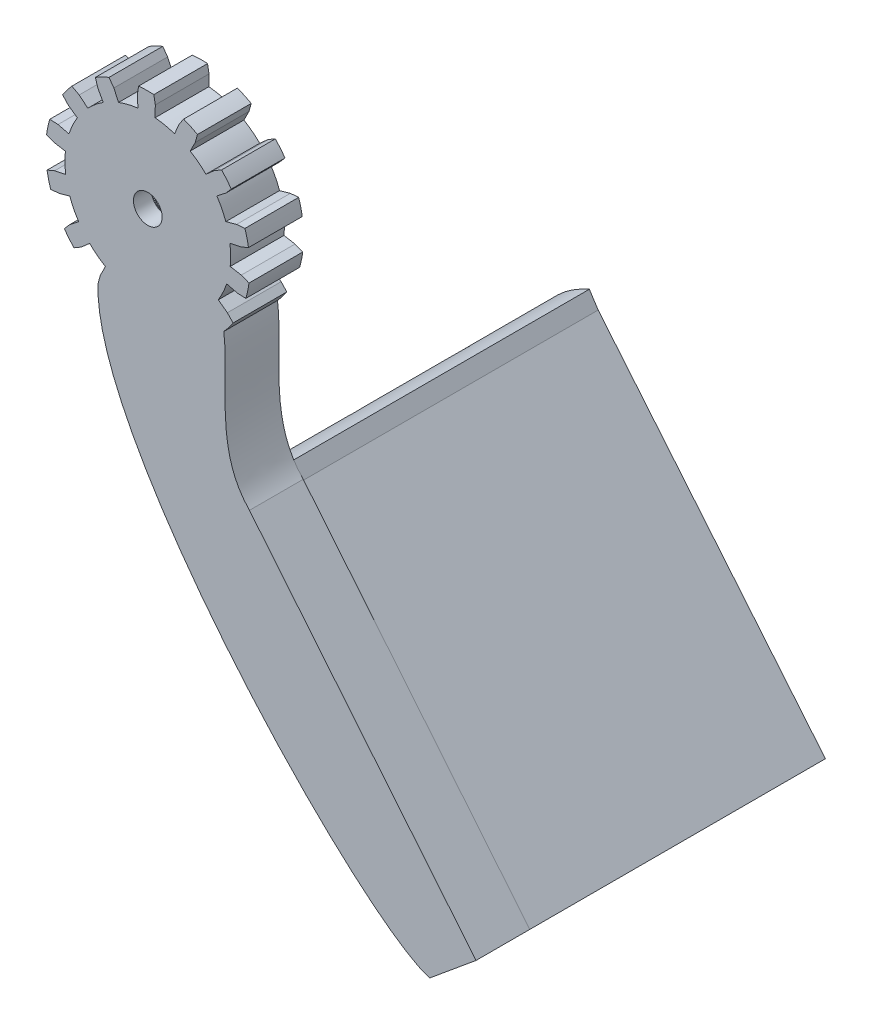
SolidWorks part; units mm, degrees
ref_plane "Front Plane" through (0, 0, 0) normal (0, 0, 1) x (1, 0, 0)
ref_plane "Top Plane" through (0, 0, 0) normal (0, 1, 0) x (1, 0, 0)
ref_plane "Right Plane" through (0, 0, 0) normal (1, 0, 0) x (0, 0, -1)
sketch "Sketch2" plane through (0, 0, 0) normal (0, 0, 1) x (1, 0, 0)
  line L0 (11.1946, 10) -> (11.1946, 10.6054) construction
  line L669 (17.6878, 7.31) -> (18.6279, 8.138)
  line L670 (18.6279, 8.138) -> (19.4304, 8.6044)
  line L671 (21.6272, -0.4657) -> (22.4922, -0.8024)
  line L672 (20.3937, -0.247) -> (21.6272, -0.4657)
  line L673 (20.3589, 1.9784) -> (21.5849, 2.2356)
  line L674 (21.5849, 2.2356) -> (22.439, 2.5991)
  line L675 (21.1094, 4.1784) -> (22.0348, 4.2505)
  line L676 (19.9032, 3.8403) -> (21.1094, 4.1784)
  line L677 (18.9062, 5.8303) -> (19.8993, 6.5939)
  line L678 (19.8993, 6.5939) -> (20.511, 7.292)
  line L679 (14.4587, -7.9329) -> (14.9822, -9.071)
  line L680 (14.9822, -9.071) -> (15.5266, -9.8227)
  line L681 (16.7705, -8.175) -> (17.0467, -9.0612)
  line L682 (16.1724, -7.0743) -> (16.7705, -8.175)
  line L683 (17.8907, -5.6595) -> (18.8561, -6.4578)
  line L684 (18.8561, -6.4578) -> (19.6729, -6.8988)
  line L685 (20.0786, -4.8746) -> (20.7119, -5.5532)
  line L686 (19.0622, -4.1424) -> (20.0786, -4.8746)
  line L687 (19.9964, -2.1222) -> (21.2126, -2.4225)
  line L688 (21.2126, -2.4225) -> (22.1398, -2.4655)
  line L689 (3.4829, -4.3861) -> (2.4899, -5.1497)
  line L690 (2.4899, -5.1497) -> (1.8781, -5.8478)
  line L691 (3.7613, -6.6939) -> (2.9588, -7.1603)
  line L692 (4.7013, -5.8658) -> (3.7613, -6.6939)
  line L693 (6.463, -7.2262) -> (5.8996, -8.3451)
  line L694 (5.8996, -8.3451) -> (5.6513, -9.2394)
  line L695 (7.7151, -9.1846) -> (7.1944, -9.953)
  line L696 (8.2027, -8.0307) -> (7.7151, -9.1846)
  line L697 (10.3802, -8.492) -> (10.3581, -9.7445)
  line L698 (10.3581, -9.7445) -> (10.5224, -10.6581)
  line L699 (12.358, -9.7133) -> (12.2223, -10.6315)
  line L700 (12.2967, -8.462) -> (12.358, -9.7133)
  line L701 (2.3105, 6.3188) -> (1.6772, 6.9974)
  line L702 (3.327, 5.5866) -> (2.3105, 6.3188)
  line L703 (2.3927, 3.5664) -> (1.1765, 3.8667)
  line L704 (1.1765, 3.8667) -> (0.2493, 3.9097)
  line L705 (0.762, 1.9099) -> (-0.103, 2.2465)
  line L706 (1.9955, 1.6912) -> (0.762, 1.9099)
  line L707 (2.0303, -0.5343) -> (0.8042, -0.7914)
  line L708 (0.8042, -0.7914) -> (-0.0498, -1.1549)
  line L709 (1.2798, -2.7343) -> (0.3543, -2.8063)
  line L710 (2.486, -2.3961) -> (1.2798, -2.7343)
  line L711 (12.009, 9.9362) -> (12.0311, 11.1887)
  line L712 (12.0311, 11.1887) -> (11.8667, 12.1023)
  line L713 (10.0311, 11.1574) -> (10.1668, 12.0757)
  line L714 (10.0924, 9.9062) -> (10.0311, 11.1574)
  line L715 (7.9305, 9.377) -> (7.4069, 10.5151)
  line L716 (7.4069, 10.5151) -> (6.8625, 11.2669)
  line L717 (5.6186, 9.6192) -> (5.3425, 10.5054)
  line L718 (6.2167, 8.5185) -> (5.6186, 9.6192)
  line L719 (4.4985, 7.1037) -> (3.533, 7.9019)
  line L720 (3.533, 7.9019) -> (2.7163, 8.343)
  line L721 (15.9262, 8.6703) -> (16.4895, 9.7892)
  line L722 (16.4895, 9.7892) -> (16.7378, 10.6836)
  line L723 (14.6741, 10.6288) -> (15.1948, 11.3972)
  line L724 (14.1864, 9.4749) -> (14.6741, 10.6288)
  arc A141 (20.511, 7.292) -> (19.4304, 8.6044) centre (11.1946, 0.7221) ccw
  arc A145 (17.6878, 7.31) -> (15.9262, 8.6703) centre (11.1946, 0.7221) ccw
  arc A149 (22.439, 2.5991) -> (22.0348, 4.2505) centre (11.1946, 0.7221) ccw
  arc A151 (22.1398, -2.4655) -> (22.4922, -0.8024) centre (11.1946, 0.7221) ccw
  arc A152 (19.6729, -6.8988) -> (20.7119, -5.5532) centre (11.1946, 0.7221) ccw
  arc A153 (15.5266, -9.8227) -> (17.0467, -9.0612) centre (11.1946, 0.7221) ccw
  arc A154 (10.5224, -10.6581) -> (12.2223, -10.6315) centre (11.1946, 0.7221) ccw
  arc A155 (5.6513, -9.2394) -> (7.1944, -9.953) centre (11.1946, 0.7221) ccw
  arc A156 (1.8781, -5.8478) -> (2.9588, -7.1603) centre (11.1946, 0.7221) ccw
  arc A157 (-0.0498, -1.1549) -> (0.3543, -2.8063) centre (11.1946, 0.7221) ccw
  arc A158 (0.2493, 3.9097) -> (-0.103, 2.2465) centre (11.1946, 0.7221) ccw
  arc A159 (2.7163, 8.343) -> (1.6772, 6.9974) centre (11.1946, 0.7221) ccw
  arc A160 (6.8625, 11.2669) -> (5.3425, 10.5054) centre (11.1946, 0.7221) ccw
  arc A161 (11.8667, 12.1023) -> (10.1668, 12.0757) centre (11.1946, 0.7221) ccw
  arc A162 (16.7378, 10.6836) -> (15.1948, 11.3972) centre (11.1946, 0.7221) ccw
  arc A163 (19.9032, 3.8403) -> (18.9062, 5.8303) centre (11.1946, 0.7221) ccw
  arc A164 (20.3937, -0.247) -> (20.3589, 1.9784) centre (11.1946, 0.7221) ccw
  arc A165 (19.0622, -4.1424) -> (19.9964, -2.1222) centre (11.1946, 0.7221) ccw
  arc A166 (16.1724, -7.0743) -> (17.8907, -5.6595) centre (11.1946, 0.7221) ccw
  arc A167 (12.2967, -8.462) -> (14.4587, -7.9329) centre (11.1946, 0.7221) ccw
  arc A168 (8.2027, -8.0307) -> (10.3802, -8.492) centre (11.1946, 0.7221) ccw
  arc A169 (4.7013, -5.8658) -> (6.463, -7.2262) centre (11.1946, 0.7221) ccw
  arc A170 (2.486, -2.3961) -> (3.4829, -4.3861) centre (11.1946, 0.7221) ccw
  arc A171 (1.9955, 1.6912) -> (2.0303, -0.5343) centre (11.1946, 0.7221) ccw
  arc A172 (3.327, 5.5866) -> (2.3927, 3.5664) centre (11.1946, 0.7221) ccw
  arc A173 (6.2167, 8.5185) -> (4.4985, 7.1037) centre (11.1946, 0.7221) ccw
  arc A174 (10.0924, 9.9062) -> (7.9305, 9.377) centre (11.1946, 0.7221) ccw
  arc A175 (14.1864, 9.4749) -> (12.009, 9.9362) centre (11.1946, 0.7221) ccw
extrude "Boss-Extrude1" add sketch "Sketch2" against normal blind 4 and the other way blind 2
sketch "Sketch3" plane through (0, 0, 2) normal (0, 0, 1) x (1, 0, 0)
  circle A0 centre (11.1946, 0) radius 3.5
  dimension "D1" = 7
extrude "Boss-Extrude2" add sketch "Sketch3" against normal blind 2
sketch "Sketch4" plane through (0, 0, 2) normal (0, 0, 1) x (1, 0, 0)
  circle A0 centre (11.1946, 0.7221) radius 4.295 construction
sketch "Sketch5" plane through (0, 0, 2) normal (0, 0, 1) x (1, 0, 0)
  line L0 (10.0276, -11.444) -> (15.4878, -11.444) construction
  line L1 (4.4176, 11.5) -> (18.1778, 11.5) construction
  line L5 (22.5424, -22.747) -> (47.8352, -53.6184)
  line L7 (42.6592, -57.9021) -> (47.8352, -53.6184)
  line L25 (15.9262, 8.6703) -> (16.4895, 9.7892)
  line L35 (3.4829, -4.3861) -> (2.4899, -5.1497)
  line L45 (15.1948, 11.3972) -> (14.6741, 10.6288)
  line L55 (14.6741, 10.6288) -> (14.1864, 9.4749)
  line L98 (22.0348, 4.2505) -> (21.1094, 4.1784)
  line L102 (12.009, 9.9362) -> (12.0311, 11.1887)
  line L104 (14.9822, -9.071) -> (15.5266, -9.8227)
  line L105 (14.9822, -9.071) -> (15.5266, -9.8227)
  line L110 (2.4899, -5.1497) -> (1.8781, -5.8478)
  line L114 (5.8996, -8.3451) -> (5.6513, -9.2394)
  line L124 (2.3927, 3.5664) -> (1.1765, 3.8667)
  line L126 (1.1765, 3.8667) -> (0.2493, 3.9097)
  line L130 (0.8042, -0.7914) -> (-0.0498, -1.1549)
  line L140 (5.3425, 10.5054) -> (5.6186, 9.6192)
  line L146 (16.4895, 9.7892) -> (16.7378, 10.6836)
  line L153 (12.0311, 11.1887) -> (11.8667, 12.1023)
  line L157 (10.1668, 12.0757) -> (10.0311, 11.1574)
  line L161 (10.0311, 11.1574) -> (10.0924, 9.9062)
  line L196 (7.9305, 9.377) -> (7.4069, 10.5151)
  line L198 (7.4069, 10.5151) -> (6.8625, 11.2669)
  line L200 (5.6186, 9.6192) -> (6.2167, 8.5185)
  line L202 (4.4985, 7.1037) -> (3.533, 7.9019)
  line L204 (3.533, 7.9019) -> (2.7163, 8.343)
  line L206 (1.6772, 6.9974) -> (2.3105, 6.3188)
  line L208 (2.3105, 6.3188) -> (3.327, 5.5866)
  line L210 (-0.103, 2.2465) -> (0.762, 1.9099)
  line L212 (0.762, 1.9099) -> (1.9955, 1.6912)
  line L214 (2.0303, -0.5343) -> (0.8042, -0.7914)
  line L216 (0.3543, -2.8063) -> (1.2798, -2.7343)
  line L218 (1.2798, -2.7343) -> (2.486, -2.3961)
  line L220 (2.9588, -7.1603) -> (3.7613, -6.6939)
  line L222 (3.7613, -6.6939) -> (4.7013, -5.8658)
  line L224 (6.463, -7.2262) -> (5.8996, -8.3451)
  line L226 (7.1944, -9.953) -> (7.7151, -9.1846)
  line L227 (7.1944, -9.953) -> (7.7151, -9.1846)
  line L228 (7.7151, -9.1846) -> (8.2027, -8.0307)
  line L229 (7.7151, -9.1846) -> (8.2027, -8.0307)
  line L230 (10.3802, -8.492) -> (10.3581, -9.7445)
  line L231 (10.3802, -8.492) -> (10.3581, -9.7445)
  line L232 (10.3581, -9.7445) -> (10.5224, -10.6581)
  line L233 (10.3581, -9.7445) -> (10.5224, -10.6581)
  line L234 (12.2223, -10.6315) -> (12.358, -9.7133)
  line L235 (12.2223, -10.6315) -> (12.358, -9.7133)
  line L236 (12.358, -9.7133) -> (12.2967, -8.462)
  line L237 (12.358, -9.7133) -> (12.2967, -8.462)
  line L238 (14.4587, -7.9329) -> (14.9822, -9.071)
  line L239 (14.4587, -7.9329) -> (14.9822, -9.071)
  line L240 (17.0467, -9.0612) -> (16.7705, -8.175)
  line L241 (17.0467, -9.0612) -> (16.7705, -8.175)
  line L242 (16.7705, -8.175) -> (16.1724, -7.0743)
  line L243 (16.7705, -8.175) -> (16.1724, -7.0743)
  line L244 (17.8907, -5.6595) -> (18.8561, -6.4578)
  line L245 (17.8907, -5.6595) -> (18.8561, -6.4578)
  line L246 (18.8561, -6.4578) -> (19.6729, -6.8988)
  line L247 (18.8561, -6.4578) -> (19.6729, -6.8988)
  line L248 (20.7119, -5.5532) -> (20.0786, -4.8746)
  line L250 (20.0786, -4.8746) -> (19.0622, -4.1424)
  line L252 (19.9964, -2.1222) -> (21.2126, -2.4225)
  line L254 (21.2126, -2.4225) -> (22.1398, -2.4655)
  line L256 (22.4922, -0.8024) -> (21.6272, -0.4657)
  line L258 (21.6272, -0.4657) -> (20.3937, -0.247)
  line L260 (20.3589, 1.9784) -> (21.5849, 2.2356)
  line L262 (21.5849, 2.2356) -> (22.439, 2.5991)
  line L264 (21.1094, 4.1784) -> (19.9032, 3.8403)
  line L266 (18.9062, 5.8303) -> (19.8993, 6.5939)
  line L268 (19.8993, 6.5939) -> (20.511, 7.292)
  line L270 (19.4304, 8.6044) -> (18.6279, 8.138)
  line L272 (18.6279, 8.138) -> (17.6878, 7.31)
  arc A14 (17.6878, 7.31) -> (15.9262, 8.6703) centre (11.1946, 0.7221) ccw
  arc A36 (16.7378, 10.6836) -> (15.1948, 11.3972) centre (11.1946, 0.7221) ccw
  arc A44 (14.1864, 9.4749) -> (12.009, 9.9362) centre (11.1946, 0.7221) ccw
  arc A52 (11.8667, 12.1023) -> (10.1668, 12.0757) centre (11.1946, 0.7221) ccw
  arc A98 (10.0924, 9.9062) -> (7.9305, 9.377) centre (11.1946, 0.7221) ccw
  arc A100 (6.8625, 11.2669) -> (5.3425, 10.5054) centre (11.1946, 0.7221) ccw
  arc A102 (6.2167, 8.5185) -> (4.4985, 7.1037) centre (11.1946, 0.7221) ccw
  arc A104 (2.7163, 8.343) -> (1.6772, 6.9974) centre (11.1946, 0.7221) ccw
  arc A106 (3.327, 5.5866) -> (2.3927, 3.5664) centre (11.1946, 0.7221) ccw
  arc A108 (0.2493, 3.9097) -> (-0.103, 2.2465) centre (11.1946, 0.7221) ccw
  arc A110 (1.9955, 1.6912) -> (2.0303, -0.5343) centre (11.1946, 0.7221) ccw
  arc A112 (-0.0498, -1.1549) -> (0.3543, -2.8063) centre (11.1946, 0.7221) ccw
  arc A114 (2.486, -2.3961) -> (3.4829, -4.3861) centre (11.1946, 0.7221) ccw
  arc A116 (1.8781, -5.8478) -> (2.9588, -7.1603) centre (11.1946, 0.7221) ccw
  arc A118 (4.7013, -5.8658) -> (6.463, -7.2262) centre (11.1946, 0.7221) ccw
  arc A120 (5.6513, -9.2394) -> (7.1944, -9.953) centre (11.1946, 0.7221) ccw
  arc A121 (5.6513, -9.2394) -> (7.1944, -9.953) centre (11.1946, 0.7221) ccw
  arc A122 (8.2027, -8.0307) -> (10.3802, -8.492) centre (11.1946, 0.7221) ccw
  arc A123 (8.2027, -8.0307) -> (10.3802, -8.492) centre (11.1946, 0.7221) ccw
  arc A124 (10.5224, -10.6581) -> (12.2223, -10.6315) centre (11.1946, 0.7221) ccw
  arc A125 (10.5224, -10.6581) -> (12.2223, -10.6315) centre (11.1946, 0.7221) ccw
  arc A126 (12.2967, -8.462) -> (14.4587, -7.9329) centre (11.1946, 0.7221) ccw
  arc A127 (12.2967, -8.462) -> (14.4587, -7.9329) centre (11.1946, 0.7221) ccw
  arc A128 (15.5266, -9.8227) -> (17.0467, -9.0612) centre (11.1946, 0.7221) ccw
  arc A129 (15.5266, -9.8227) -> (17.0467, -9.0612) centre (11.1946, 0.7221) ccw
  arc A130 (16.1724, -7.0743) -> (17.8907, -5.6595) centre (11.1946, 0.7221) ccw
  arc A131 (16.1724, -7.0743) -> (17.8907, -5.6595) centre (11.1946, 0.7221) ccw
  arc A132 (19.6729, -6.8988) -> (20.7119, -5.5532) centre (11.1946, 0.7221) ccw
  arc A134 (19.0622, -4.1424) -> (19.9964, -2.1222) centre (11.1946, 0.7221) ccw
  arc A136 (22.1398, -2.4655) -> (22.4922, -0.8024) centre (11.1946, 0.7221) ccw
  arc A138 (20.3937, -0.247) -> (20.3589, 1.9784) centre (11.1946, 0.7221) ccw
  arc A140 (22.439, 2.5991) -> (22.0348, 4.2505) centre (11.1946, 0.7221) ccw
  arc A142 (19.9032, 3.8403) -> (18.9062, 5.8303) centre (11.1946, 0.7221) ccw
  arc A144 (20.511, 7.292) -> (19.4304, 8.6044) centre (11.1946, 0.7221) ccw
  spline S0 degree 3 poles (19.6729, -6.8988) (20.3229, -11.6834) (18.5625, -18.6883) (22.5424, -22.747) knots 0 0 0 0 1 1 1 1
  spline S1 degree 3 poles (42.6592, -57.9021) (34.7948, -55.7125) (4.8913, -24.2389) (5.6513, -9.2394) knots 0.222416 0.222416 0.222416 0.222416 1 1 1 1
  dimension "D1" = 0
extrude "Boss-Extrude3" add sketch "Sketch5" against normal up to surface (6 mm away) up to face at (11.1946, 0.7221, -4)
sketch "Sketch6" plane through (0, 0, -4) normal (0, 0, -1) x (-1, 0, 0)
  line L0 (-47.8352, -53.6184) -> (-22.4699, -22.9253)
  line L24 (-2.4899, -5.1497) -> (-3.4829, -4.3861)
  line L32 (-22.5424, -22.747) -> (-47.8352, -53.6184)
  line L86 (-47.8352, -53.6184) -> (-42.6592, -57.9021)
  line L88 (-47.8352, -53.6184) -> (-42.6592, -57.9021)
  line L141 (-16.7378, 10.6836) -> (-16.4895, 9.7892)
  line L147 (-5.6186, 9.6192) -> (-5.3425, 10.5054)
  line L157 (0.0498, -1.1549) -> (-0.8042, -0.7914)
  line L161 (-0.2493, 3.9097) -> (-1.1765, 3.8667)
  line L163 (-1.1765, 3.8667) -> (-2.3927, 3.5664)
  line L173 (-5.6513, -9.2394) -> (-5.8996, -8.3451)
  line L177 (-1.8781, -5.8478) -> (-2.4899, -5.1497)
  line L206 (-21.1094, 4.1784) -> (-22.0348, 4.2505)
  line L208 (-17.6878, 7.31) -> (-18.6279, 8.138)
  line L210 (-18.6279, 8.138) -> (-19.4304, 8.6044)
  line L212 (-20.511, 7.292) -> (-19.8993, 6.5939)
  line L214 (-19.8993, 6.5939) -> (-18.9062, 5.8303)
  line L216 (-19.9032, 3.8403) -> (-21.1094, 4.1784)
  line L218 (-22.439, 2.5991) -> (-21.5849, 2.2356)
  line L220 (-21.5849, 2.2356) -> (-20.3589, 1.9784)
  line L222 (-20.3937, -0.247) -> (-21.6272, -0.4657)
  line L224 (-21.6272, -0.4657) -> (-22.4922, -0.8024)
  line L226 (-22.1398, -2.4655) -> (-21.2126, -2.4225)
  line L228 (-21.2126, -2.4225) -> (-19.9964, -2.1222)
  line L230 (-19.0622, -4.1424) -> (-20.0786, -4.8746)
  line L232 (-20.0786, -4.8746) -> (-20.7119, -5.5532)
  line L256 (-5.8996, -8.3451) -> (-6.463, -7.2262)
  line L258 (-4.7013, -5.8658) -> (-3.7613, -6.6939)
  line L260 (-3.7613, -6.6939) -> (-2.9588, -7.1603)
  line L262 (-2.486, -2.3961) -> (-1.2798, -2.7343)
  line L264 (-1.2798, -2.7343) -> (-0.3543, -2.8063)
  line L266 (-0.8042, -0.7914) -> (-2.0303, -0.5343)
  line L268 (-1.9955, 1.6912) -> (-0.762, 1.9099)
  line L270 (-0.762, 1.9099) -> (0.103, 2.2465)
  line L272 (-3.327, 5.5866) -> (-2.3105, 6.3188)
  line L274 (-2.3105, 6.3188) -> (-1.6772, 6.9974)
  line L276 (-2.7163, 8.343) -> (-3.533, 7.9019)
  line L278 (-3.533, 7.9019) -> (-4.4985, 7.1037)
  line L280 (-6.2167, 8.5185) -> (-5.6186, 9.6192)
  line L282 (-6.8625, 11.2669) -> (-7.4069, 10.5151)
  line L284 (-7.4069, 10.5151) -> (-7.9305, 9.377)
  line L286 (-10.0924, 9.9062) -> (-10.0311, 11.1574)
  line L288 (-10.0311, 11.1574) -> (-10.1668, 12.0757)
  line L290 (-11.8667, 12.1023) -> (-12.0311, 11.1887)
  line L292 (-12.0311, 11.1887) -> (-12.009, 9.9362)
  line L294 (-14.1864, 9.4749) -> (-14.6741, 10.6288)
  line L296 (-14.6741, 10.6288) -> (-15.1948, 11.3972)
  line L298 (-16.4895, 9.7892) -> (-15.9262, 8.6703)
  arc A44 (-15.9262, 8.6703) -> (-17.6878, 7.31) centre (-11.1946, 0.7221) ccw
  arc A85 (-19.4304, 8.6044) -> (-20.511, 7.292) centre (-11.1946, 0.7221) ccw
  arc A87 (-18.9062, 5.8303) -> (-19.9032, 3.8403) centre (-11.1946, 0.7221) ccw
  arc A89 (-22.0348, 4.2505) -> (-22.439, 2.5991) centre (-11.1946, 0.7221) ccw
  arc A91 (-20.3589, 1.9784) -> (-20.3937, -0.247) centre (-11.1946, 0.7221) ccw
  arc A93 (-22.4922, -0.8024) -> (-22.1398, -2.4655) centre (-11.1946, 0.7221) ccw
  arc A95 (-19.9964, -2.1222) -> (-19.0622, -4.1424) centre (-11.1946, 0.7221) ccw
  arc A97 (-20.7119, -5.5532) -> (-19.6729, -6.8988) centre (-11.1946, 0.7221) ccw
  arc A111 (-6.463, -7.2262) -> (-4.7013, -5.8658) centre (-11.1946, 0.7221) ccw
  arc A113 (-2.9588, -7.1603) -> (-1.8781, -5.8478) centre (-11.1946, 0.7221) ccw
  arc A115 (-3.4829, -4.3861) -> (-2.486, -2.3961) centre (-11.1946, 0.7221) ccw
  arc A117 (-0.3543, -2.8063) -> (0.0498, -1.1549) centre (-11.1946, 0.7221) ccw
  arc A119 (-2.0303, -0.5343) -> (-1.9955, 1.6912) centre (-11.1946, 0.7221) ccw
  arc A121 (0.103, 2.2465) -> (-0.2493, 3.9097) centre (-11.1946, 0.7221) ccw
  arc A123 (-2.3927, 3.5664) -> (-3.327, 5.5866) centre (-11.1946, 0.7221) ccw
  arc A125 (-1.6772, 6.9974) -> (-2.7163, 8.343) centre (-11.1946, 0.7221) ccw
  arc A127 (-4.4985, 7.1037) -> (-6.2167, 8.5185) centre (-11.1946, 0.7221) ccw
  arc A129 (-5.3425, 10.5054) -> (-6.8625, 11.2669) centre (-11.1946, 0.7221) ccw
  arc A131 (-7.9305, 9.377) -> (-10.0924, 9.9062) centre (-11.1946, 0.7221) ccw
  arc A133 (-10.1668, 12.0757) -> (-11.8667, 12.1023) centre (-11.1946, 0.7221) ccw
  arc A135 (-12.009, 9.9362) -> (-14.1864, 9.4749) centre (-11.1946, 0.7221) ccw
  arc A137 (-15.1948, 11.3972) -> (-16.7378, 10.6836) centre (-11.1946, 0.7221) ccw
  spline S0 degree 2 poles (-21.4843, -21.4053) (-15.4608, -24.0435) (-14.9342, -30.624) knots 0 0 0 1 1 1
  spline S1 degree 1 poles (-21.4843, -21.4053) (-22.4699, -22.9253) knots 0 0 1 1
  spline S2 degree 3 poles (2049.8624, 2090.3676) (-2456.4303, -2304.2529) (2542.9708, 2077.6557) (-2472.1397, -1711.8889) knots -2.171759 -2.171759 -2.171759 -2.171759 3.412488 3.412488 3.412488 3.412488 only from (-42.6592, -57.9021) to (-5.6513, -9.2394) construction
  spline S4 degree 3 poles (-42.6592, -57.9021) (-37.7406, -56.5327) (-24.2012, -43.7085) (-14.9342, -30.624) knots 0.222416 0.222416 0.222416 0.222416 0.708738 0.708738 0.708738 0.708738
  spline S6 degree 3 poles (837.4917, -521.9394) (-890.8689, 582.5241) (863.9486, -583.6115) (-915.3049, 427.7689) knots -4.426358 -4.426358 -4.426358 -4.426358 5.086809 5.086809 5.086809 5.086809 only from (-19.6729, -6.8988) to (-22.5424, -22.747)
  spline S7 degree 3 poles (630.5716, 681.5226) (-904.3184, -885.7477) (926.9509, 733.4176) (-861.5437, -526.3532) knots -1.362805 -1.362805 -1.362805 -1.362805 2.601902 2.601902 2.601902 2.601902 only from (-42.6592, -57.9021) to (-5.6513, -9.2394)
  dimension "D1" = 0
extrude "Boss-Extrude4" add sketch "Sketch6" along normal blind 33
sketch "Sketch7" plane through (0, 0, -4) normal (0, 0, -1) x (-1, 0, 0)
  line L200 (-13.2071, 2.8678) -> (-13.1729, 2.7035)
  line L201 (-13.0453, 2.8231) -> (-13.2071, 2.8678)
  line L202 (-13.0691, 2.9892) -> (-13.0453, 2.8231)
  line L203 (-12.9105, 2.9344) -> (-13.0691, 2.9892)
  line L204 (-12.9238, 3.1017) -> (-12.9105, 2.9344)
  line L205 (-12.769, 3.0371) -> (-12.9238, 3.1017)
  line L206 (-12.7717, 3.2048) -> (-12.769, 3.0371)
  line L207 (-12.6213, 3.1306) -> (-12.7717, 3.2048)
  line L208 (-12.6135, 3.2982) -> (-12.6213, 3.1306)
  line L209 (-12.468, 3.2147) -> (-12.6135, 3.2982)
  line L210 (-12.4497, 3.3814) -> (-12.468, 3.2147)
  line L211 (-12.3097, 3.289) -> (-12.4497, 3.3814)
  line L212 (-12.281, 3.4543) -> (-12.3097, 3.289)
  line L213 (-12.1471, 3.3532) -> (-12.281, 3.4543)
  line L214 (-12.108, 3.5163) -> (-12.1471, 3.3532)
  line L215 (-11.9807, 3.407) -> (-12.108, 3.5163)
  line L216 (-11.9315, 3.5674) -> (-11.9807, 3.407)
  line L217 (-11.8113, 3.4504) -> (-11.9315, 3.5674)
  line L218 (-11.7521, 3.6073) -> (-11.8113, 3.4504)
  line L219 (-11.6396, 3.4829) -> (-11.7521, 3.6073)
  line L220 (-11.5706, 3.6359) -> (-11.6396, 3.4829)
  line L221 (-11.4661, 3.5047) -> (-11.5706, 3.6359)
  line L222 (-11.3877, 3.653) -> (-11.4661, 3.5047)
  line L223 (-11.2916, 3.5155) -> (-11.3877, 3.653)
  line L224 (-11.204, 3.6586) -> (-11.2916, 3.5155)
  line L225 (-11.1167, 3.5153) -> (-11.204, 3.6586)
  line L226 (-11.0204, 3.6527) -> (-11.1167, 3.5153)
  line L227 (-10.9422, 3.5042) -> (-11.0204, 3.6527)
  line L228 (-10.8374, 3.6352) -> (-10.9422, 3.5042)
  line L229 (-10.7688, 3.4821) -> (-10.8374, 3.6352)
  line L230 (-10.656, 3.6063) -> (-10.7688, 3.4821)
  line L231 (-10.5971, 3.4492) -> (-10.656, 3.6063)
  line L232 (-10.4767, 3.566) -> (-10.5971, 3.4492)
  line L233 (-10.4278, 3.4055) -> (-10.4767, 3.566)
  line L234 (-10.3003, 3.5146) -> (-10.4278, 3.4055)
  line L235 (-10.2616, 3.3513) -> (-10.3003, 3.5146)
  line L236 (-10.1275, 3.4522) -> (-10.2616, 3.3513)
  line L237 (-10.0991, 3.2868) -> (-10.1275, 3.4522)
  line L238 (-9.9589, 3.379) -> (-10.0991, 3.2868)
  line L239 (-9.9409, 3.2122) -> (-9.9589, 3.379)
  line L240 (-9.7953, 3.2954) -> (-9.9409, 3.2122)
  line L241 (-9.7878, 3.1278) -> (-9.7953, 3.2954)
  line L242 (-9.6372, 3.2018) -> (-9.7878, 3.1278)
  line L243 (-9.6403, 3.034) -> (-9.6372, 3.2018)
  line L244 (-9.4853, 3.0983) -> (-9.6403, 3.034)
  line L245 (-9.4989, 2.9311) -> (-9.4853, 3.0983)
  line L246 (-9.3402, 2.9856) -> (-9.4989, 2.9311)
  line L247 (-9.3643, 2.8195) -> (-9.3402, 2.9856)
  line L248 (-9.2025, 2.8639) -> (-9.3643, 2.8195)
  line L249 (-9.237, 2.6997) -> (-9.2025, 2.8639)
  line L250 (-9.0727, 2.7339) -> (-9.237, 2.6997)
  line L251 (-9.1174, 2.5721) -> (-9.0727, 2.7339)
  line L252 (-8.9513, 2.5959) -> (-9.1174, 2.5721)
  line L253 (-9.0061, 2.4373) -> (-8.9513, 2.5959)
  line L254 (-8.8388, 2.4506) -> (-9.0061, 2.4373)
  line L255 (-8.9035, 2.2958) -> (-8.8388, 2.4506)
  line L256 (-8.7357, 2.2985) -> (-8.9035, 2.2958)
  line L257 (-8.8099, 2.1481) -> (-8.7357, 2.2985)
  line L258 (-8.6423, 2.1403) -> (-8.8099, 2.1481)
  line L259 (-8.7258, 1.9948) -> (-8.6423, 2.1403)
  line L260 (-8.5591, 1.9765) -> (-8.7258, 1.9948)
  line L261 (-8.6515, 1.8365) -> (-8.5591, 1.9765)
  line L262 (-8.4862, 1.8078) -> (-8.6515, 1.8365)
  line L263 (-8.5873, 1.6739) -> (-8.4862, 1.8078)
  line L264 (-8.4242, 1.6348) -> (-8.5873, 1.6739)
  line L265 (-8.5335, 1.5075) -> (-8.4242, 1.6348)
  line L266 (-8.3731, 1.4583) -> (-8.5335, 1.5075)
  line L267 (-8.4902, 1.3381) -> (-8.3731, 1.4583)
  line L268 (-8.3332, 1.2789) -> (-8.4902, 1.3381)
  line L269 (-8.4576, 1.1664) -> (-8.3332, 1.2789)
  line L270 (-8.3046, 1.0974) -> (-8.4576, 1.1664)
  line L271 (-8.4358, 0.9929) -> (-8.3046, 1.0974)
  line L272 (-8.2875, 0.9145) -> (-8.4358, 0.9929)
  line L273 (-8.425, 0.8184) -> (-8.2875, 0.9145)
  line L274 (-8.2819, 0.7308) -> (-8.425, 0.8184)
  line L275 (-8.4252, 0.6435) -> (-8.2819, 0.7308)
  line L276 (-8.2878, 0.5471) -> (-8.4252, 0.6435)
  line L277 (-8.4363, 0.469) -> (-8.2878, 0.5471)
  line L278 (-8.3053, 0.3642) -> (-8.4363, 0.469)
  line L279 (-8.4584, 0.2956) -> (-8.3053, 0.3642)
  line L280 (-8.3342, 0.1828) -> (-8.4584, 0.2956)
  line L281 (-8.4913, 0.1239) -> (-8.3342, 0.1828)
  line L282 (-8.3745, 0.0035) -> (-8.4913, 0.1239)
  line L283 (-8.535, -0.0454) -> (-8.3745, 0.0035)
  line L284 (-8.4259, -0.1729) -> (-8.535, -0.0454)
  line L285 (-8.5892, -0.2117) -> (-8.4259, -0.1729)
  line L286 (-8.4883, -0.3457) -> (-8.5892, -0.2117)
  line L287 (-8.6537, -0.3742) -> (-8.4883, -0.3457)
  line L288 (-8.5615, -0.5143) -> (-8.6537, -0.3742)
  line L289 (-8.7283, -0.5323) -> (-8.5615, -0.5143)
  line L290 (-8.6451, -0.678) -> (-8.7283, -0.5323)
  line L291 (-8.8127, -0.6854) -> (-8.6451, -0.678)
  line L292 (-8.7388, -0.836) -> (-8.8127, -0.6854)
  line L293 (-8.9065, -0.8329) -> (-8.7388, -0.836)
  line L294 (-8.8422, -0.9879) -> (-8.9065, -0.8329)
  line L295 (-9.0094, -0.9743) -> (-8.8422, -0.9879)
  line L296 (-8.9549, -1.133) -> (-9.0094, -0.9743)
  line L297 (-9.121, -1.1089) -> (-8.9549, -1.133)
  line L298 (-9.0766, -1.2707) -> (-9.121, -1.1089)
  line L299 (-9.2408, -1.2362) -> (-9.0766, -1.2707)
  line L300 (-9.2067, -1.4005) -> (-9.2408, -1.2362)
  line L301 (-9.3684, -1.3558) -> (-9.2067, -1.4005)
  line L302 (-9.3446, -1.5219) -> (-9.3684, -1.3558)
  line L303 (-9.5032, -1.4671) -> (-9.3446, -1.5219)
  line L304 (-9.4899, -1.6344) -> (-9.5032, -1.4671)
  line L305 (-9.6447, -1.5698) -> (-9.4899, -1.6344)
  line L306 (-9.642, -1.7375) -> (-9.6447, -1.5698)
  line L307 (-9.7925, -1.6633) -> (-9.642, -1.7375)
  line L308 (-9.8002, -1.8309) -> (-9.7925, -1.6633)
  line L309 (-9.9458, -1.7474) -> (-9.8002, -1.8309)
  line L310 (-9.964, -1.9141) -> (-9.9458, -1.7474)
  line L311 (-10.104, -1.8217) -> (-9.964, -1.9141)
  line L312 (-10.1328, -1.987) -> (-10.104, -1.8217)
  line L313 (-10.2667, -1.8859) -> (-10.1328, -1.987)
  line L314 (-10.3057, -2.049) -> (-10.2667, -1.8859)
  line L315 (-10.433, -1.9397) -> (-10.3057, -2.049)
  line L316 (-10.4822, -2.1001) -> (-10.433, -1.9397)
  line L317 (-10.6024, -1.9831) -> (-10.4822, -2.1001)
  line L318 (-10.6616, -2.14) -> (-10.6024, -1.9831)
  line L319 (-10.7742, -2.0156) -> (-10.6616, -2.14)
  line L320 (-10.8431, -2.1686) -> (-10.7742, -2.0156)
  line L321 (-10.9476, -2.0374) -> (-10.8431, -2.1686)
  line L322 (-11.026, -2.1857) -> (-10.9476, -2.0374)
  line L323 (-11.1221, -2.0482) -> (-11.026, -2.1857)
  line L324 (-11.2097, -2.1913) -> (-11.1221, -2.0482)
  line L325 (-11.297, -2.048) -> (-11.2097, -2.1913)
  line L326 (-11.3934, -2.1854) -> (-11.297, -2.048)
  line L327 (-11.4715, -2.0369) -> (-11.3934, -2.1854)
  line L328 (-11.5763, -2.1679) -> (-11.4715, -2.0369)
  line L329 (-11.6449, -2.0148) -> (-11.5763, -2.1679)
  line L330 (-11.7577, -2.139) -> (-11.6449, -2.0148)
  line L331 (-11.8166, -1.9819) -> (-11.7577, -2.139)
  line L332 (-11.937, -2.0987) -> (-11.8166, -1.9819)
  line L333 (-11.9859, -1.9382) -> (-11.937, -2.0987)
  line L334 (-12.1134, -2.0473) -> (-11.9859, -1.9382)
  line L335 (-12.1522, -1.884) -> (-12.1134, -2.0473)
  line L336 (-12.2863, -1.9849) -> (-12.1522, -1.884)
  line L337 (-12.3147, -1.8195) -> (-12.2863, -1.9849)
  line L338 (-12.4548, -1.9117) -> (-12.3147, -1.8195)
  line L339 (-12.4728, -1.7449) -> (-12.4548, -1.9117)
  line L340 (-12.6185, -1.8281) -> (-12.4728, -1.7449)
  line L341 (-12.6259, -1.6605) -> (-12.6185, -1.8281)
  line L342 (-12.7765, -1.7345) -> (-12.6259, -1.6605)
  line L343 (-12.7735, -1.5667) -> (-12.7765, -1.7345)
  line L344 (-12.9284, -1.631) -> (-12.7735, -1.5667)
  line L345 (-12.9148, -1.4638) -> (-12.9284, -1.631)
  line L346 (-13.0735, -1.5183) -> (-12.9148, -1.4638)
  line L347 (-13.0494, -1.3522) -> (-13.0735, -1.5183)
  line L348 (-13.2112, -1.3966) -> (-13.0494, -1.3522)
  line L349 (-13.1767, -1.2324) -> (-13.2112, -1.3966)
  line L350 (-13.341, -1.2665) -> (-13.1767, -1.2324)
  line L351 (-13.2963, -1.1048) -> (-13.341, -1.2665)
  line L352 (-13.4624, -1.1286) -> (-13.2963, -1.1048)
  line L353 (-13.4076, -0.97) -> (-13.4624, -1.1286)
  line L354 (-13.5749, -0.9833) -> (-13.4076, -0.97)
  line L355 (-13.5103, -0.8285) -> (-13.5749, -0.9833)
  line L356 (-13.678, -0.8312) -> (-13.5103, -0.8285)
  line L357 (-13.6038, -0.6808) -> (-13.678, -0.8312)
  line L358 (-13.7714, -0.673) -> (-13.6038, -0.6808)
  line L359 (-13.6879, -0.5275) -> (-13.7714, -0.673)
  line L360 (-13.8547, -0.5092) -> (-13.6879, -0.5275)
  line L361 (-13.7622, -0.3692) -> (-13.8547, -0.5092)
  line L362 (-13.9275, -0.3405) -> (-13.7622, -0.3692)
  line L363 (-13.8264, -0.2066) -> (-13.9275, -0.3405)
  line L364 (-13.9895, -0.1675) -> (-13.8264, -0.2066)
  line L365 (-13.8802, -0.0402) -> (-13.9895, -0.1675)
  line L366 (-14.0406, 0.009) -> (-13.8802, -0.0402)
  line L367 (-13.9236, 0.1292) -> (-14.0406, 0.009)
  line L368 (-14.0805, 0.1884) -> (-13.9236, 0.1292)
  line L369 (-13.9562, 0.3009) -> (-14.0805, 0.1884)
  line L370 (-14.1091, 0.3699) -> (-13.9562, 0.3009)
  line L371 (-13.9779, 0.4744) -> (-14.1091, 0.3699)
  line L372 (-14.1262, 0.5528) -> (-13.9779, 0.4744)
  line L373 (-13.9887, 0.6489) -> (-14.1262, 0.5528)
  line L374 (-14.1318, 0.7365) -> (-13.9887, 0.6489)
  line L375 (-13.9885, 0.8238) -> (-14.1318, 0.7365)
  line L376 (-14.1259, 0.9202) -> (-13.9885, 0.8238)
  line L377 (-13.9774, 0.9983) -> (-14.1259, 0.9202)
  line L378 (-14.1084, 1.1031) -> (-13.9774, 0.9983)
  line L379 (-13.9553, 1.1717) -> (-14.1084, 1.1031)
  line L380 (-14.0795, 1.2845) -> (-13.9553, 1.1717)
  line L381 (-13.9224, 1.3434) -> (-14.0795, 1.2845)
  line L382 (-14.0392, 1.4638) -> (-13.9224, 1.3434)
  line L383 (-13.8787, 1.5127) -> (-14.0392, 1.4638)
  line L384 (-13.9878, 1.6402) -> (-13.8787, 1.5127)
  line L385 (-13.8245, 1.679) -> (-13.9878, 1.6402)
  line L386 (-13.9254, 1.813) -> (-13.8245, 1.679)
  line L387 (-13.76, 1.8415) -> (-13.9254, 1.813)
  line L388 (-13.8522, 1.9816) -> (-13.76, 1.8415)
  line L389 (-13.6854, 1.9996) -> (-13.8522, 1.9816)
  line L390 (-13.7687, 2.1453) -> (-13.6854, 1.9996)
  line L391 (-13.601, 2.1527) -> (-13.7687, 2.1453)
  line L392 (-13.675, 2.3033) -> (-13.601, 2.1527)
  line L393 (-13.5072, 2.3002) -> (-13.675, 2.3033)
  line L394 (-13.5715, 2.4552) -> (-13.5072, 2.3002)
  line L395 (-13.4043, 2.4416) -> (-13.5715, 2.4552)
  line L396 (-13.4588, 2.6003) -> (-13.4043, 2.4416)
  line L397 (-13.2927, 2.5762) -> (-13.4588, 2.6003)
  line L398 (-13.3371, 2.738) -> (-13.2927, 2.5762)
  line L399 (-13.1729, 2.7035) -> (-13.3371, 2.738)
  line L400 (-13.2071, 2.8678) -> (-13.1729, 2.7035)
  line L401 (-13.0453, 2.8231) -> (-13.2071, 2.8678)
  line L402 (-13.0691, 2.9892) -> (-13.0453, 2.8231)
  line L403 (-12.9105, 2.9344) -> (-13.0691, 2.9892)
  line L404 (-12.9238, 3.1017) -> (-12.9105, 2.9344)
  line L405 (-12.769, 3.0371) -> (-12.9238, 3.1017)
  line L406 (-12.7717, 3.2048) -> (-12.769, 3.0371)
  line L407 (-12.6213, 3.1306) -> (-12.7717, 3.2048)
  line L408 (-12.6135, 3.2982) -> (-12.6213, 3.1306)
  line L409 (-12.468, 3.2147) -> (-12.6135, 3.2982)
  line L410 (-12.4497, 3.3814) -> (-12.468, 3.2147)
  line L411 (-12.3097, 3.289) -> (-12.4497, 3.3814)
  line L412 (-12.281, 3.4543) -> (-12.3097, 3.289)
  line L413 (-12.1471, 3.3532) -> (-12.281, 3.4543)
  line L414 (-12.108, 3.5163) -> (-12.1471, 3.3532)
  line L415 (-11.9807, 3.407) -> (-12.108, 3.5163)
  line L416 (-11.9315, 3.5674) -> (-11.9807, 3.407)
  line L417 (-11.8113, 3.4504) -> (-11.9315, 3.5674)
  line L418 (-11.7521, 3.6073) -> (-11.8113, 3.4504)
  line L419 (-11.6396, 3.4829) -> (-11.7521, 3.6073)
  line L420 (-11.5706, 3.6359) -> (-11.6396, 3.4829)
  line L421 (-11.4661, 3.5047) -> (-11.5706, 3.6359)
  line L422 (-11.3877, 3.653) -> (-11.4661, 3.5047)
  line L423 (-11.2916, 3.5155) -> (-11.3877, 3.653)
  line L424 (-11.204, 3.6586) -> (-11.2916, 3.5155)
  line L425 (-11.1167, 3.5153) -> (-11.204, 3.6586)
  line L426 (-11.0204, 3.6527) -> (-11.1167, 3.5153)
  line L427 (-10.9422, 3.5042) -> (-11.0204, 3.6527)
  line L428 (-10.8374, 3.6352) -> (-10.9422, 3.5042)
  line L429 (-10.7688, 3.4821) -> (-10.8374, 3.6352)
  line L430 (-10.656, 3.6063) -> (-10.7688, 3.4821)
  line L431 (-10.5971, 3.4492) -> (-10.656, 3.6063)
  line L432 (-10.4767, 3.566) -> (-10.5971, 3.4492)
  line L433 (-10.4278, 3.4055) -> (-10.4767, 3.566)
  line L434 (-10.3003, 3.5146) -> (-10.4278, 3.4055)
  line L435 (-10.2616, 3.3513) -> (-10.3003, 3.5146)
  line L436 (-10.1275, 3.4522) -> (-10.2616, 3.3513)
  line L437 (-10.0991, 3.2868) -> (-10.1275, 3.4522)
  line L438 (-9.9589, 3.379) -> (-10.0991, 3.2868)
  line L439 (-9.9409, 3.2122) -> (-9.9589, 3.379)
  line L440 (-9.7953, 3.2954) -> (-9.9409, 3.2122)
  line L441 (-9.7878, 3.1278) -> (-9.7953, 3.2954)
  line L442 (-9.6372, 3.2018) -> (-9.7878, 3.1278)
  line L443 (-9.6403, 3.034) -> (-9.6372, 3.2018)
  line L444 (-9.4853, 3.0983) -> (-9.6403, 3.034)
  line L445 (-9.4989, 2.9311) -> (-9.4853, 3.0983)
  line L446 (-9.3402, 2.9856) -> (-9.4989, 2.9311)
  line L447 (-9.3643, 2.8195) -> (-9.3402, 2.9856)
  line L448 (-9.2025, 2.8639) -> (-9.3643, 2.8195)
  line L449 (-9.237, 2.6997) -> (-9.2025, 2.8639)
  line L450 (-9.0727, 2.7339) -> (-9.237, 2.6997)
  line L451 (-9.1174, 2.5721) -> (-9.0727, 2.7339)
  line L452 (-8.9513, 2.5959) -> (-9.1174, 2.5721)
  line L453 (-9.0061, 2.4373) -> (-8.9513, 2.5959)
  line L454 (-8.8388, 2.4506) -> (-9.0061, 2.4373)
  line L455 (-8.9035, 2.2958) -> (-8.8388, 2.4506)
  line L456 (-8.7357, 2.2985) -> (-8.9035, 2.2958)
  line L457 (-8.8099, 2.1481) -> (-8.7357, 2.2985)
  line L458 (-8.6423, 2.1403) -> (-8.8099, 2.1481)
  line L459 (-8.7258, 1.9948) -> (-8.6423, 2.1403)
  line L460 (-8.5591, 1.9765) -> (-8.7258, 1.9948)
  line L461 (-8.6515, 1.8365) -> (-8.5591, 1.9765)
  line L462 (-8.4862, 1.8078) -> (-8.6515, 1.8365)
  line L463 (-8.5873, 1.6739) -> (-8.4862, 1.8078)
  line L464 (-8.4242, 1.6348) -> (-8.5873, 1.6739)
  line L465 (-8.5335, 1.5075) -> (-8.4242, 1.6348)
  line L466 (-8.3731, 1.4583) -> (-8.5335, 1.5075)
  line L467 (-8.4902, 1.3381) -> (-8.3731, 1.4583)
  line L468 (-8.3332, 1.2789) -> (-8.4902, 1.3381)
  line L469 (-8.4576, 1.1664) -> (-8.3332, 1.2789)
  line L470 (-8.3046, 1.0974) -> (-8.4576, 1.1664)
  line L471 (-8.4358, 0.9929) -> (-8.3046, 1.0974)
  line L472 (-8.2875, 0.9145) -> (-8.4358, 0.9929)
  line L473 (-8.425, 0.8184) -> (-8.2875, 0.9145)
  line L474 (-8.2819, 0.7308) -> (-8.425, 0.8184)
  line L475 (-8.4252, 0.6435) -> (-8.2819, 0.7308)
  line L476 (-8.2878, 0.5471) -> (-8.4252, 0.6435)
  line L477 (-8.4363, 0.469) -> (-8.2878, 0.5471)
  line L478 (-8.3053, 0.3642) -> (-8.4363, 0.469)
  line L479 (-8.4584, 0.2956) -> (-8.3053, 0.3642)
  line L480 (-8.3342, 0.1828) -> (-8.4584, 0.2956)
  line L481 (-8.4913, 0.1239) -> (-8.3342, 0.1828)
  line L482 (-8.3745, 0.0035) -> (-8.4913, 0.1239)
  line L483 (-8.535, -0.0454) -> (-8.3745, 0.0035)
  line L484 (-8.4259, -0.1729) -> (-8.535, -0.0454)
  line L485 (-8.5892, -0.2117) -> (-8.4259, -0.1729)
  line L486 (-8.4883, -0.3457) -> (-8.5892, -0.2117)
  line L487 (-8.6537, -0.3742) -> (-8.4883, -0.3457)
  line L488 (-8.5615, -0.5143) -> (-8.6537, -0.3742)
  line L489 (-8.7283, -0.5323) -> (-8.5615, -0.5143)
  line L490 (-8.6451, -0.678) -> (-8.7283, -0.5323)
  line L491 (-8.8127, -0.6854) -> (-8.6451, -0.678)
  line L492 (-8.7388, -0.836) -> (-8.8127, -0.6854)
  line L493 (-8.9065, -0.8329) -> (-8.7388, -0.836)
  line L494 (-8.8422, -0.9879) -> (-8.9065, -0.8329)
  line L495 (-9.0094, -0.9743) -> (-8.8422, -0.9879)
  line L496 (-8.9549, -1.133) -> (-9.0094, -0.9743)
  line L497 (-9.121, -1.1089) -> (-8.9549, -1.133)
  line L498 (-9.0766, -1.2707) -> (-9.121, -1.1089)
  line L499 (-9.2408, -1.2362) -> (-9.0766, -1.2707)
  line L500 (-9.2067, -1.4005) -> (-9.2408, -1.2362)
  line L501 (-9.3684, -1.3558) -> (-9.2067, -1.4005)
  line L502 (-9.3446, -1.5219) -> (-9.3684, -1.3558)
  line L503 (-9.5032, -1.4671) -> (-9.3446, -1.5219)
  line L504 (-9.4899, -1.6344) -> (-9.5032, -1.4671)
  line L505 (-9.6447, -1.5698) -> (-9.4899, -1.6344)
  line L506 (-9.642, -1.7375) -> (-9.6447, -1.5698)
  line L507 (-9.7925, -1.6633) -> (-9.642, -1.7375)
  line L508 (-9.8002, -1.8309) -> (-9.7925, -1.6633)
  line L509 (-9.9458, -1.7474) -> (-9.8002, -1.8309)
  line L510 (-9.964, -1.9141) -> (-9.9458, -1.7474)
  line L511 (-10.104, -1.8217) -> (-9.964, -1.9141)
  line L512 (-10.1328, -1.987) -> (-10.104, -1.8217)
  line L513 (-10.2667, -1.8859) -> (-10.1328, -1.987)
  line L514 (-10.3057, -2.049) -> (-10.2667, -1.8859)
  line L515 (-10.433, -1.9397) -> (-10.3057, -2.049)
  line L516 (-10.4822, -2.1001) -> (-10.433, -1.9397)
  line L517 (-10.6024, -1.9831) -> (-10.4822, -2.1001)
  line L518 (-10.6616, -2.14) -> (-10.6024, -1.9831)
  line L519 (-10.7742, -2.0156) -> (-10.6616, -2.14)
  line L520 (-10.8431, -2.1686) -> (-10.7742, -2.0156)
  line L521 (-10.9476, -2.0374) -> (-10.8431, -2.1686)
  line L522 (-11.026, -2.1857) -> (-10.9476, -2.0374)
  line L523 (-11.1221, -2.0482) -> (-11.026, -2.1857)
  line L524 (-11.2097, -2.1913) -> (-11.1221, -2.0482)
  line L525 (-11.297, -2.048) -> (-11.2097, -2.1913)
  line L526 (-11.3934, -2.1854) -> (-11.297, -2.048)
  line L527 (-11.4715, -2.0369) -> (-11.3934, -2.1854)
  line L528 (-11.5763, -2.1679) -> (-11.4715, -2.0369)
  line L529 (-11.6449, -2.0148) -> (-11.5763, -2.1679)
  line L530 (-11.7577, -2.139) -> (-11.6449, -2.0148)
  line L531 (-11.8166, -1.9819) -> (-11.7577, -2.139)
  line L532 (-11.937, -2.0987) -> (-11.8166, -1.9819)
  line L533 (-11.9859, -1.9382) -> (-11.937, -2.0987)
  line L534 (-12.1134, -2.0473) -> (-11.9859, -1.9382)
  line L535 (-12.1522, -1.884) -> (-12.1134, -2.0473)
  line L536 (-12.2863, -1.9849) -> (-12.1522, -1.884)
  line L537 (-12.3147, -1.8195) -> (-12.2863, -1.9849)
  line L538 (-12.4548, -1.9117) -> (-12.3147, -1.8195)
  line L539 (-12.4728, -1.7449) -> (-12.4548, -1.9117)
  line L540 (-12.6185, -1.8281) -> (-12.4728, -1.7449)
  line L541 (-12.6259, -1.6605) -> (-12.6185, -1.8281)
  line L542 (-12.7765, -1.7345) -> (-12.6259, -1.6605)
  line L543 (-12.7735, -1.5667) -> (-12.7765, -1.7345)
  line L544 (-12.9284, -1.631) -> (-12.7735, -1.5667)
  line L545 (-12.9148, -1.4638) -> (-12.9284, -1.631)
  line L546 (-13.0735, -1.5183) -> (-12.9148, -1.4638)
  line L547 (-13.0494, -1.3522) -> (-13.0735, -1.5183)
  line L548 (-13.2112, -1.3966) -> (-13.0494, -1.3522)
  line L549 (-13.1767, -1.2324) -> (-13.2112, -1.3966)
  line L550 (-13.341, -1.2665) -> (-13.1767, -1.2324)
  line L551 (-13.2963, -1.1048) -> (-13.341, -1.2665)
  line L552 (-13.4624, -1.1286) -> (-13.2963, -1.1048)
  line L553 (-13.4076, -0.97) -> (-13.4624, -1.1286)
  line L554 (-13.5749, -0.9833) -> (-13.4076, -0.97)
  line L555 (-13.5103, -0.8285) -> (-13.5749, -0.9833)
  line L556 (-13.678, -0.8312) -> (-13.5103, -0.8285)
  line L557 (-13.6038, -0.6808) -> (-13.678, -0.8312)
  line L558 (-13.7714, -0.673) -> (-13.6038, -0.6808)
  line L559 (-13.6879, -0.5275) -> (-13.7714, -0.673)
  line L560 (-13.8547, -0.5092) -> (-13.6879, -0.5275)
  line L561 (-13.7622, -0.3692) -> (-13.8547, -0.5092)
  line L562 (-13.9275, -0.3405) -> (-13.7622, -0.3692)
  line L563 (-13.8264, -0.2066) -> (-13.9275, -0.3405)
  line L564 (-13.9895, -0.1675) -> (-13.8264, -0.2066)
  line L565 (-13.8802, -0.0402) -> (-13.9895, -0.1675)
  line L566 (-14.0406, 0.009) -> (-13.8802, -0.0402)
  line L567 (-13.9236, 0.1292) -> (-14.0406, 0.009)
  line L568 (-14.0805, 0.1884) -> (-13.9236, 0.1292)
  line L569 (-13.9562, 0.3009) -> (-14.0805, 0.1884)
  line L570 (-14.1091, 0.3699) -> (-13.9562, 0.3009)
  line L571 (-13.9779, 0.4744) -> (-14.1091, 0.3699)
  line L572 (-14.1262, 0.5528) -> (-13.9779, 0.4744)
  line L573 (-13.9887, 0.6489) -> (-14.1262, 0.5528)
  line L574 (-14.1318, 0.7365) -> (-13.9887, 0.6489)
  line L575 (-13.9885, 0.8238) -> (-14.1318, 0.7365)
  line L576 (-14.1259, 0.9202) -> (-13.9885, 0.8238)
  line L577 (-13.9774, 0.9983) -> (-14.1259, 0.9202)
  line L578 (-14.1084, 1.1031) -> (-13.9774, 0.9983)
  line L579 (-13.9553, 1.1717) -> (-14.1084, 1.1031)
  line L580 (-14.0795, 1.2845) -> (-13.9553, 1.1717)
  line L581 (-13.9224, 1.3434) -> (-14.0795, 1.2845)
  line L582 (-14.0392, 1.4638) -> (-13.9224, 1.3434)
  line L583 (-13.8787, 1.5127) -> (-14.0392, 1.4638)
  line L584 (-13.9878, 1.6402) -> (-13.8787, 1.5127)
  line L585 (-13.8245, 1.679) -> (-13.9878, 1.6402)
  line L586 (-13.9254, 1.813) -> (-13.8245, 1.679)
  line L587 (-13.76, 1.8415) -> (-13.9254, 1.813)
  line L588 (-13.8522, 1.9816) -> (-13.76, 1.8415)
  line L589 (-13.6854, 1.9996) -> (-13.8522, 1.9816)
  line L590 (-13.7687, 2.1453) -> (-13.6854, 1.9996)
  line L591 (-13.601, 2.1527) -> (-13.7687, 2.1453)
  line L592 (-13.675, 2.3033) -> (-13.601, 2.1527)
  line L593 (-13.5072, 2.3002) -> (-13.675, 2.3033)
  line L594 (-13.5715, 2.4552) -> (-13.5072, 2.3002)
  line L595 (-13.4043, 2.4416) -> (-13.5715, 2.4552)
  line L596 (-13.4588, 2.6003) -> (-13.4043, 2.4416)
  line L597 (-13.2927, 2.5762) -> (-13.4588, 2.6003)
  line L598 (-13.3371, 2.738) -> (-13.2927, 2.5762)
  line L599 (-13.1729, 2.7035) -> (-13.3371, 2.738)
  dimension "D1" = 0
extrude "Cut-Extrude1" cut sketch "Sketch7" against normal offset from surface (4 mm away) 2
sketch "Sketch8" plane through (0, 0, -4) normal (0, 0, -1) x (-1, 0, 0)
  circle A0 centre (-11.1946, 0.7221) radius 1.6
  dimension "D1" = 3.2
extrude "Cut-Extrude2" cut sketch "Sketch8" against normal blind 8
